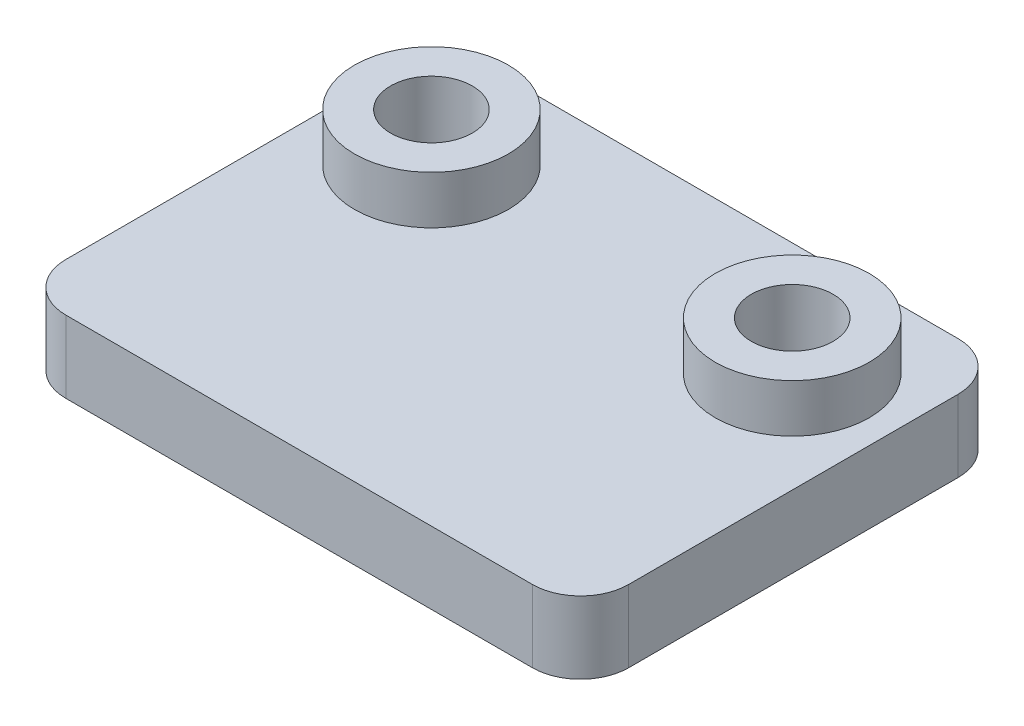
SolidWorks part; units mm, degrees
material "PLA"
ref_plane "Спереди" through (0, 0, 0) normal (0, 0, 1) x (1, 0, 0)
ref_plane "Сверху" through (0, 0, 0) normal (0, 1, 0) x (1, 0, 0)
ref_plane "Справа" through (0, 0, 0) normal (1, 0, 0) x (0, 0, -1)
sketch "Эскиз1" plane through (0, 0, 0) normal (0, 1, 0) x (1, 0, 0)
  line L0 (0, 28.3329) -> (0, -31.9613) construction
  line L1 (-32.738, 0) -> (35.5416, 0) construction
  line L7 (-11.7, 4.7) -> (11.7, 4.7)
  line L8 (-11.7, 4.7) -> (-11.7, -13)
  line L9 (-11.7, -13) -> (11.7, -13)
  line L10 (11.7, 4.7) -> (11.7, -13)
  circle A0 centre (-7.5, 0) radius 1.7
  circle A1 centre (7.5, 0) radius 1.7
  point P9 (0, 0)
  point P14 (0, 4.7)
  dimension "D1" = 3.4
  dimension "D3" = 3
  dimension "D4" = 2.5
  dimension "D5" = 13
  dimension "D2" = 15
extrude "Бобышка-Вытянуть1" add sketch "Эскиз1" along normal blind 3
sketch "Эскиз2" plane through (0, 3, 0) normal (0, 1, 0) x (1, 0, 0)
  circle A0 centre (-7.5, 0) radius 3.2
  circle A1 centre (7.5, 0) radius 3.2
  circle A2 centre (-7.5, 0) radius 1.7 construction
  circle A3 centre (7.5, 0) radius 1.7 construction
  circle A4 centre (7.5, 0) radius 1.7
  circle A5 centre (-7.5, 0) radius 1.7
  dimension "D1" = 1.5
extrude "Бобышка-Вытянуть2" add sketch "Эскиз2" along normal blind 2
fillet "Скругление1" radius 2 4 edges at (11.7, 1.5, 13) (-11.7, 1.5, 13) (-11.7, 1.5, -4.7) (11.7, 1.5, -4.7)
